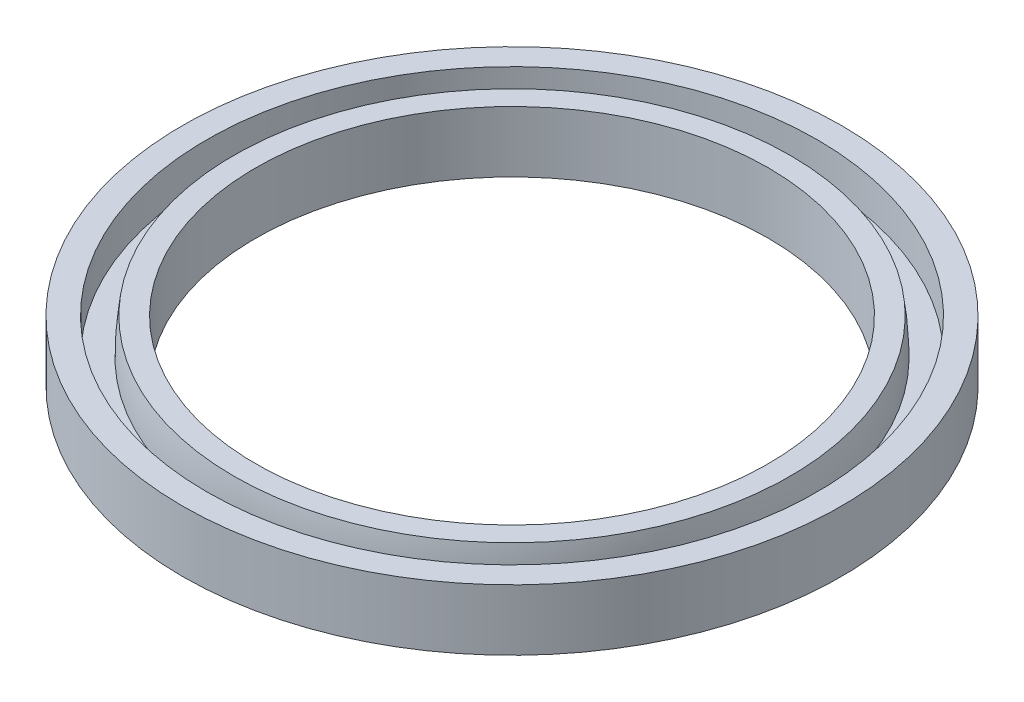
SolidWorks part; units mm, degrees
ref_plane "Front Plane" through (0, 0, 0) normal (0, 0, 1) x (1, 0, 0)
ref_plane "Top Plane" through (0, 0, 0) normal (0, 1, 0) x (1, 0, 0)
ref_plane "Right Plane" through (0, 0, 0) normal (1, 0, 0) x (0, 0, -1)
sketch "Sketch1" plane through (0, 0, 0) normal (1, 0, 0) x (0, 0, -1)
  line L0 (0, -564.5896) -> (0, 27664.8881) construction
  line L1 (-564.5896, 0) -> (27664.8881, 0) construction
  line L2 (25, 3) -> (27, 3)
  line L3 (21, 3) -> (22.7785, 3)
  line L4 (21, 3) -> (21, -2)
  line L5 (21, -2) -> (27, -2)
  line L6 (27, 3) -> (27, -2)
  line L9 (23, 0) -> (25, 0)
  line L10 (25, 3) -> (25, 0)
  line L11 (22.7785, 3) -> (22.8206, 3) construction
  arc A2 (25, 0) -> (0, 25) centre (0, 0) ccw construction
  arc A3 (23, 0) -> (0, 23) centre (0, 0) ccw construction
  arc A5 (22.7785, 3) -> (23, 0) centre (2.5724, 0) cw
  point P14 (22.8035, 3)
  dimension "D1" = 6
  dimension "D6" = 0.025
  dimension "D4" = 2
  dimension "D2" = 5
  dimension "D3" = 2
  dimension "D5" = 2
revolve "Revolve1" add sketch "Sketch1" angle 360 about L0
